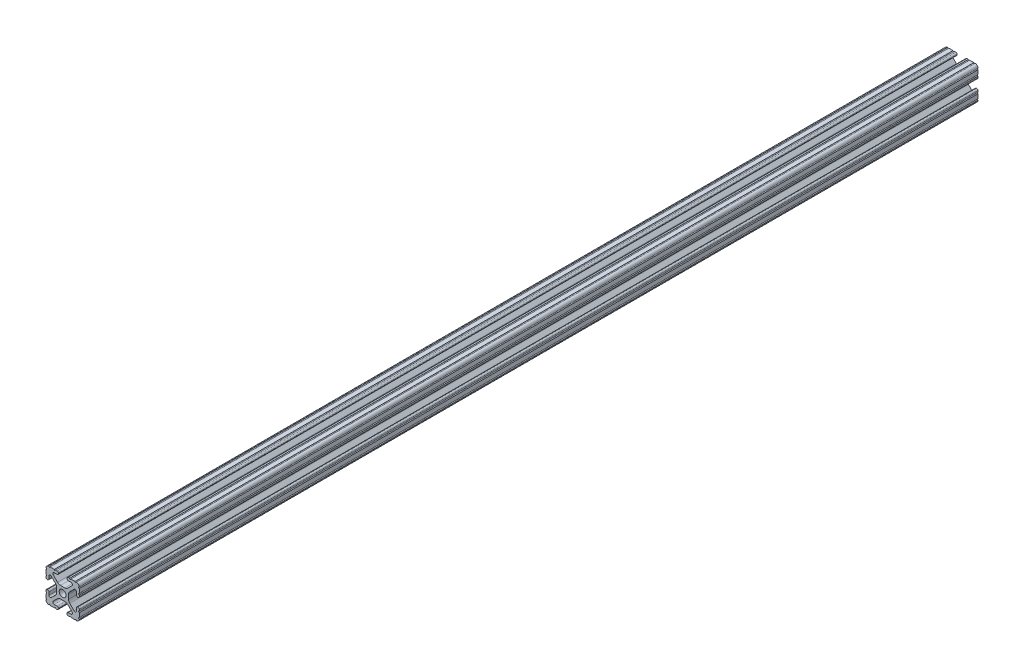
SolidWorks part; units mm, degrees
ref_plane "Front Plane" through (0, 0, 0) normal (0, 0, 1) x (1, 0, 0)
ref_plane "Top Plane" through (0, 0, 0) normal (0, 1, 0) x (1, 0, 0)
ref_plane "Right Plane" through (0, 0, 0) normal (1, 0, 0) x (0, 0, -1)
sketch "Sketch1" plane through (0, 0, 0) normal (0, 0, 1) x (1, 0, 0)
  line L88 (-7.1797, -8.6452) -> (-3.9523, -5.4237)
  line L89 (-1.7093, -4.4958) -> (1.7093, -4.4958)
  line L90 (3.9523, -5.4237) -> (7.1797, -8.6452)
  line L91 (6.4164, -10.4902) -> (4.2875, -10.4902)
  line L92 (3.2385, -11.5392) -> (3.2385, -11.651)
  line L93 (4.2875, -12.7) -> (5.3171, -12.7)
  line L94 (6.3331, -12.7) -> (9.5504, -12.7)
  line L95 (12.7, -9.5504) -> (12.7, -6.3331)
  line L96 (12.7, -5.3171) -> (12.7, -4.2875)
  line L97 (11.651, -3.2385) -> (11.5392, -3.2385)
  line L98 (10.4902, -4.2875) -> (10.4902, -6.4021)
  line L99 (8.7371, -7.1294) -> (5.441, -3.8408)
  line L100 (4.5085, -1.5932) -> (4.5085, 1.5932)
  line L101 (5.441, 3.8408) -> (8.7371, 7.1294)
  line L102 (10.4902, 6.4021) -> (10.4902, 4.2875)
  line L103 (11.5392, 3.2385) -> (11.651, 3.2385)
  line L104 (12.7, 4.2875) -> (12.7, 5.3171)
  line L105 (12.7, 6.3331) -> (12.7, 9.5504)
  line L106 (9.5504, 12.7) -> (6.3331, 12.7)
  line L107 (5.3171, 12.7) -> (4.2875, 12.7)
  line L108 (3.2385, 11.651) -> (3.2385, 11.5392)
  line L109 (4.2875, 10.4902) -> (6.4768, 10.4902)
  line L110 (7.207, 8.7244) -> (3.8983, 5.4232)
  line L111 (1.6558, 4.4958) -> (-1.6558, 4.4958)
  line L112 (-3.8983, 5.4232) -> (-7.207, 8.7244)
  line L113 (-6.4768, 10.4902) -> (-4.2875, 10.4902)
  line L114 (-3.2385, 11.5392) -> (-3.2385, 11.651)
  line L115 (-4.2875, 12.7) -> (-5.3171, 12.7)
  line L116 (-6.3331, 12.7) -> (-9.5504, 12.7)
  line L117 (-12.7, 9.5504) -> (-12.7, 6.3331)
  line L118 (-12.7, 5.3171) -> (-12.7, 4.2875)
  line L119 (-11.651, 3.2385) -> (-11.5392, 3.2385)
  line L120 (-10.4902, 4.2875) -> (-10.4902, 6.4021)
  line L121 (-8.7371, 7.1294) -> (-5.441, 3.8408)
  line L122 (-4.5085, 1.5932) -> (-4.5085, -1.5932)
  line L123 (-5.441, -3.8408) -> (-8.7371, -7.1294)
  line L124 (-10.4902, -6.4021) -> (-10.4902, -4.2875)
  line L125 (-11.5392, -3.2385) -> (-11.651, -3.2385)
  line L126 (-12.7, -4.2875) -> (-12.7, -5.3171)
  line L127 (-12.7, -6.3331) -> (-12.7, -9.5504)
  line L128 (-9.5504, -12.7) -> (-6.3331, -12.7)
  line L129 (-5.3171, -12.7) -> (-4.2875, -12.7)
  line L130 (-3.2385, -11.651) -> (-3.2385, -11.5392)
  line L131 (-4.2875, -10.4902) -> (-6.4164, -10.4902)
  circle A1 centre (0, 0) radius 2.6035
  arc A104 (-7.1797, -8.6452) -> (-6.4164, -10.4902) centre (-6.4164, -9.4098) ccw
  arc A105 (-1.7093, -4.4958) -> (-3.9523, -5.4237) centre (-1.7093, -7.6708) ccw
  arc A106 (3.9523, -5.4237) -> (1.7093, -4.4958) centre (1.7093, -7.6708) ccw
  arc A107 (6.4164, -10.4902) -> (7.1797, -8.6452) centre (6.4164, -9.4098) ccw
  arc A108 (4.2875, -10.4902) -> (3.2385, -11.5392) centre (4.2875, -11.5392) ccw
  arc A109 (3.2385, -11.651) -> (4.2875, -12.7) centre (4.2875, -11.651) ccw
  arc A110 (6.3331, -12.7) -> (5.3171, -12.7) centre (5.8251, -12.7) ccw
  arc A111 (10.5664, -12.6998) -> (9.5504, -12.7) centre (10.0584, -12.7) ccw
  arc A112 (10.5664, -12.6998) -> (12.6998, -10.5664) centre (10.5918, -10.5918) ccw
  arc A113 (12.7, -9.5504) -> (12.6998, -10.5664) centre (12.7, -10.0584) ccw
  arc A114 (12.7, -5.3171) -> (12.7, -6.3331) centre (12.7, -5.8251) ccw
  arc A115 (12.7, -4.2875) -> (11.651, -3.2385) centre (11.651, -4.2875) ccw
  arc A116 (11.5392, -3.2385) -> (10.4902, -4.2875) centre (11.5392, -4.2875) ccw
  arc A117 (8.7371, -7.1294) -> (10.4902, -6.4021) centre (9.4628, -6.4021) ccw
  arc A118 (4.5085, -1.5932) -> (5.441, -3.8408) centre (7.6835, -1.5932) ccw
  arc A119 (5.441, 3.8408) -> (4.5085, 1.5932) centre (7.6835, 1.5932) ccw
  arc A120 (10.4902, 6.4021) -> (8.7371, 7.1294) centre (9.4628, 6.4021) ccw
  arc A121 (10.4902, 4.2875) -> (11.5392, 3.2385) centre (11.5392, 4.2875) ccw
  arc A122 (11.651, 3.2385) -> (12.7, 4.2875) centre (11.651, 4.2875) ccw
  arc A123 (12.7, 6.3331) -> (12.7, 5.3171) centre (12.7, 5.8251) ccw
  arc A124 (12.6998, 10.5664) -> (12.7, 9.5504) centre (12.7, 10.0584) ccw
  arc A125 (12.6998, 10.5664) -> (10.5664, 12.6998) centre (10.5918, 10.5918) ccw
  arc A126 (9.5504, 12.7) -> (10.5664, 12.6998) centre (10.0584, 12.7) ccw
  arc A127 (5.3171, 12.7) -> (6.3331, 12.7) centre (5.8251, 12.7) ccw
  arc A128 (4.2875, 12.7) -> (3.2385, 11.651) centre (4.2875, 11.651) ccw
  arc A129 (3.2385, 11.5392) -> (4.2875, 10.4902) centre (4.2875, 11.5392) ccw
  arc A130 (7.207, 8.7244) -> (6.4768, 10.4902) centre (6.4768, 9.4563) ccw
  arc A131 (1.6558, 4.4958) -> (3.8983, 5.4232) centre (1.6558, 7.6708) ccw
  arc A132 (-3.8983, 5.4232) -> (-1.6558, 4.4958) centre (-1.6558, 7.6708) ccw
  arc A133 (-6.4768, 10.4902) -> (-7.207, 8.7244) centre (-6.4768, 9.4563) ccw
  arc A134 (-4.2875, 10.4902) -> (-3.2385, 11.5392) centre (-4.2875, 11.5392) ccw
  arc A135 (-3.2385, 11.651) -> (-4.2875, 12.7) centre (-4.2875, 11.651) ccw
  arc A136 (-6.3331, 12.7) -> (-5.3171, 12.7) centre (-5.8251, 12.7) ccw
  arc A137 (-10.5664, 12.6998) -> (-9.5504, 12.7) centre (-10.0584, 12.7) ccw
  arc A138 (-10.5664, 12.6998) -> (-12.6998, 10.5664) centre (-10.5918, 10.5918) ccw
  arc A139 (-12.7, 9.5504) -> (-12.6998, 10.5664) centre (-12.7, 10.0584) ccw
  arc A140 (-12.7, 5.3171) -> (-12.7, 6.3331) centre (-12.7, 5.8251) ccw
  arc A141 (-12.7, 4.2875) -> (-11.651, 3.2385) centre (-11.651, 4.2875) ccw
  arc A142 (-11.5392, 3.2385) -> (-10.4902, 4.2875) centre (-11.5392, 4.2875) ccw
  arc A143 (-8.7371, 7.1294) -> (-10.4902, 6.4021) centre (-9.4628, 6.4021) ccw
  arc A144 (-4.5085, 1.5932) -> (-5.441, 3.8408) centre (-7.6835, 1.5932) ccw
  arc A145 (-5.441, -3.8408) -> (-4.5085, -1.5932) centre (-7.6835, -1.5932) ccw
  arc A146 (-10.4902, -6.4021) -> (-8.7371, -7.1294) centre (-9.4628, -6.4021) ccw
  arc A147 (-10.4902, -4.2875) -> (-11.5392, -3.2385) centre (-11.5392, -4.2875) ccw
  arc A148 (-11.651, -3.2385) -> (-12.7, -4.2875) centre (-11.651, -4.2875) ccw
  arc A149 (-12.7, -6.3331) -> (-12.7, -5.3171) centre (-12.7, -5.8251) ccw
  arc A150 (-12.6998, -10.5664) -> (-12.7, -9.5504) centre (-12.7, -10.0584) ccw
  arc A151 (-12.6998, -10.5664) -> (-10.5664, -12.6998) centre (-10.5918, -10.5918) ccw
  arc A152 (-9.5504, -12.7) -> (-10.5664, -12.6998) centre (-10.0584, -12.7) ccw
  arc A153 (-5.3171, -12.7) -> (-6.3331, -12.7) centre (-5.8251, -12.7) ccw
  arc A154 (-4.2875, -12.7) -> (-3.2385, -11.651) centre (-4.2875, -11.651) ccw
  arc A155 (-3.2385, -11.5392) -> (-4.2875, -10.4902) centre (-4.2875, -11.5392) ccw
extrude "Boss-Extrude1" add sketch "Sketch1" along normal mid plane 685.8
